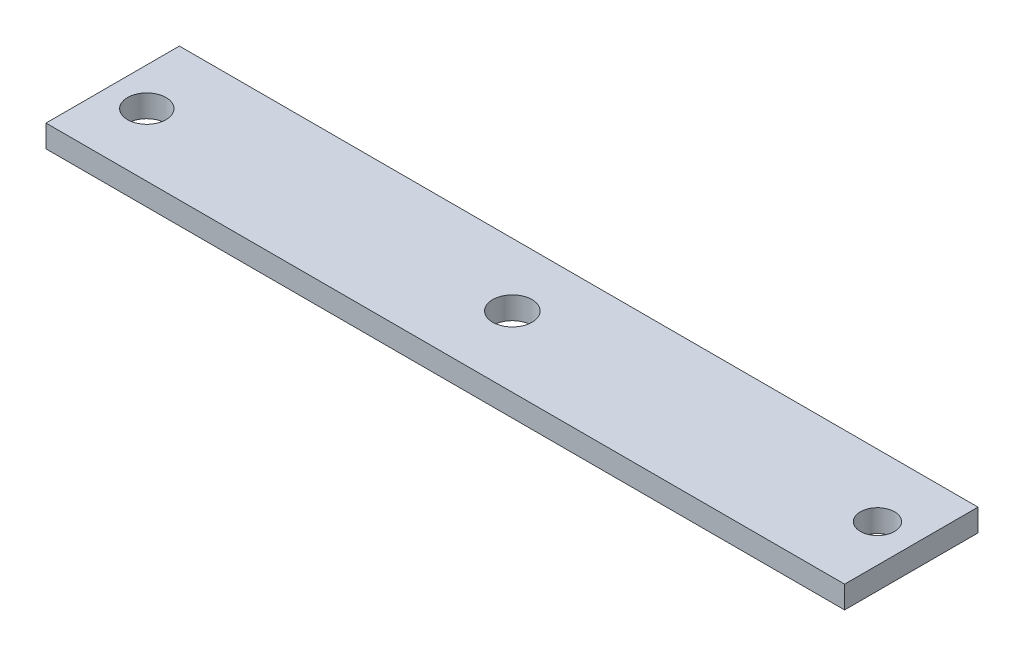
SolidWorks part; units mm, degrees
ref_plane "Front Plane" through (0, 0, 0) normal (0, 0, 1) x (1, 0, 0)
ref_plane "Top Plane" through (0, 0, 0) normal (0, 1, 0) x (1, 0, 0)
ref_plane "Right Plane" through (0, 0, 0) normal (1, 0, 0) x (0, 0, -1)
sketch "Sketch1" plane through (0, 0, 0) normal (0, 1, 0) x (1, 0, 0)
  line L1 (-33.3681, 8.8802) -> (59.4319, 8.8802)
  line L2 (-33.3681, 8.8802) -> (-33.3681, -6.6198)
  line L3 (-33.3681, -6.6198) -> (59.4319, -6.6198)
  line L4 (59.4319, 8.8802) -> (59.4319, -6.6198)
  circle A0 centre (-28.9681, 0.6902) radius 2.2355
  circle A1 centre (12.6319, 1.5702) radius 2.285
  circle A2 centre (55.0519, 1.5802) radius 1.985
  dimension "D5" = 4.471
  dimension "D8" = 4.57
  dimension "D11" = 3.97
  dimension "D1" = 15.5
  dimension "D2" = 92.8
  dimension "D3" = 7.31
  dimension "D4" = 4.4
  dimension "D6" = 46
  dimension "D7" = 8.19
  dimension "D9" = 88.42
  dimension "D10" = 8.2
extrude "Boss-Extrude1" add sketch "Sketch1" along normal blind 2.6
